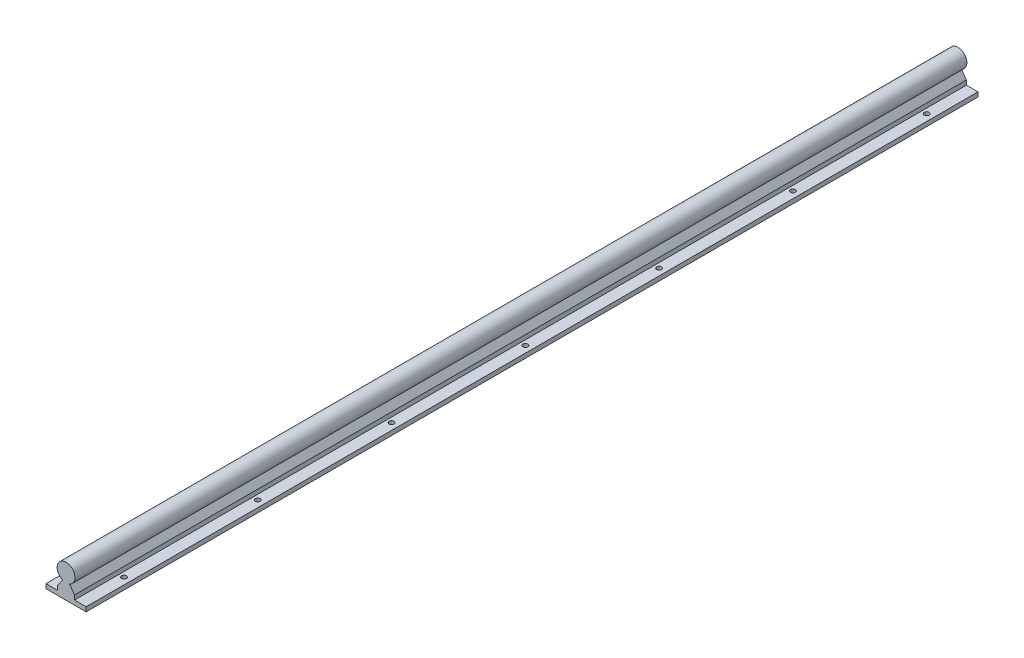
SolidWorks part; units mm, degrees
ref_plane "前视基准面" through (0, 0, 0) normal (0, 0, 1) x (1, 0, 0)
ref_plane "上视基准面" through (0, 0, 0) normal (0, 1, 0) x (1, 0, 0)
ref_plane "右视基准面" through (0, 0, 0) normal (1, 0, 0) x (0, 0, -1)
other "Configuration Table"
sketch "草图1" plane through (0, 0, 0) normal (0, 0, 1) x (1, 0, 0)
  line L0 (-22.5, 0) -> (22.5, 0)
  line L1 (22.5, 0) -> (22.5, 5)
  line L2 (22.5, 5) -> (9.5, 5)
  line L4 (0, 0) -> (0, 17)
  line L5 (3.6756, 17.7) -> (4, 17.7)
  line L6 (0, 0) -> (0, 17)
  line L7 (4, 17.7) -> (9.5, 10)
  line L8 (-9.5, 10) -> (-9.5, 5)
  line L9 (9.5, 10) -> (9.5, 5)
  line L10 (-4, 17.7) -> (-9.5, 10)
  line L11 (-3.6756, 17.7) -> (-4, 17.7)
  line L12 (-22.5, 5) -> (-9.5, 5)
  line L13 (-22.5, 0) -> (-22.5, 5)
  circle A0 centre (0, 27) radius 10
  dimension "D1" = 4
  dimension "D6" = 20
  dimension "D2" = 17.7
  dimension "D3" = 10
  dimension "D4" = 5
  dimension "D5" = 9.5
  dimension "D7" = 27
  dimension "D8" = 45
extrude "凸台-拉伸1" add sketch "草图1" along normal blind 1000 contours A0 | A0 L11 L10 L8 L12 L13 L0 L4 | A0 L4 L0 L1 L2 L9 L7 L5
sketch "草图2" plane through (0, 0, 0) normal (0, 1, 0) x (1, 0, 0)
  line L0 (22.5, -500) -> (-22.5, -500)
  line L1 (22.5, -1000) -> (22.5, 0) construction
  line L2 (-22.5, -1000) -> (-22.5, 0) construction
  line L3 (0, -500) -> (-15, -500)
  line L4 (0, -500) -> (15, -500)
  line L5 (15, -500) -> (15, -650) construction
  circle A0 centre (-15, -500) radius 2.75
  circle A1 centre (15, -500) radius 2.75
  circle A2 centre (15, -650) radius 2.75
  circle A3 centre (-15, -650) radius 2.75
  circle A4 centre (15, -350) radius 2.75
  circle A5 centre (-15, -350) radius 2.75
  circle A6 centre (-15, -350) radius 2.75
  circle A7 centre (15, -350) radius 2.75
  circle A8 centre (-15, -200) radius 2.75
  circle A9 centre (15, -200) radius 2.75
  circle A10 centre (-15, -50) radius 2.75
  circle A11 centre (15, -50) radius 2.75
  circle A12 centre (-15, -650) radius 2.75
  circle A13 centre (15, -650) radius 2.75
  circle A14 centre (-15, -800) radius 2.75
  circle A15 centre (15, -800) radius 2.75
  circle A16 centre (-15, -950) radius 2.75
  circle A17 centre (15, -950) radius 2.75
  dimension "D3" = 2
  dimension "D1" = 30
  dimension "D2" = 15
  dimension "D4" = 150
  dimension "D5" = 2
  dimension "D6" = 4
  dimension "D7" = 4
extrude "切除-拉伸2" cut sketch "草图2" along normal blind 450
